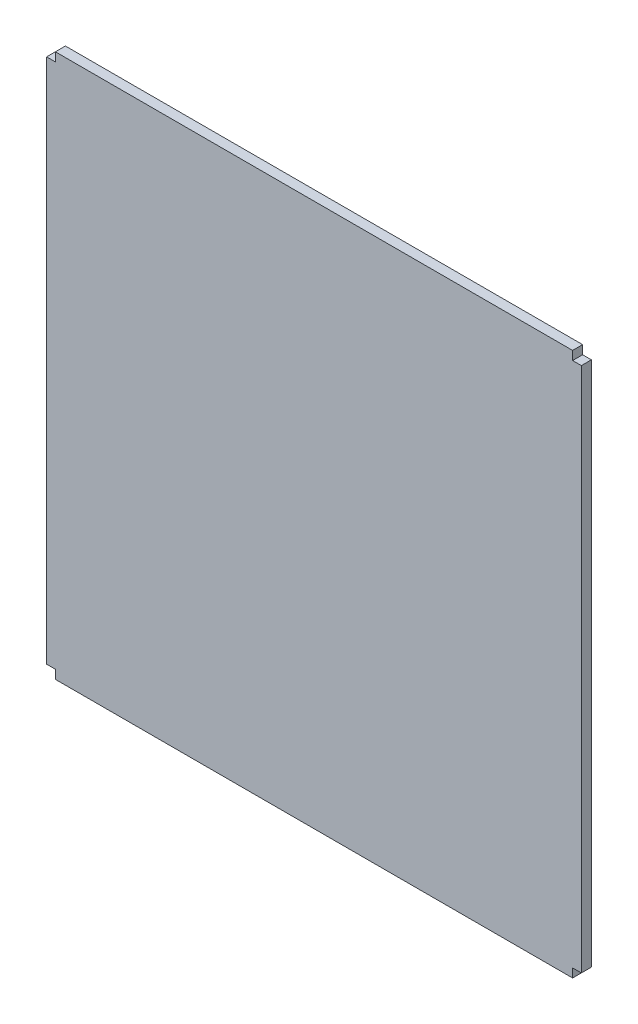
SolidWorks part; units mm, degrees
ref_plane "Ön Düzlem" through (0, 0, 0) normal (0, 0, 1) x (1, 0, 0)
ref_plane "Üst Düzlem" through (0, 0, 0) normal (0, 1, 0) x (1, 0, 0)
ref_plane "Sağ Düzlem" through (0, 0, 0) normal (1, 0, 0) x (0, 0, -1)
sketch "Sketch1" plane through (0, 0, 0) normal (0, 0, 1) x (1, 0, 0)
  line L5 (-213.5, -217) -> (213.5, -217)
  line L6 (-213.5, -217) -> (-213.5, 217)
  line L7 (-213.5, 217) -> (213.5, 217)
  line L8 (213.5, -217) -> (213.5, 217)
  line L9 (-213.5, -217) -> (213.5, 217) construction
  line L10 (-213.5, 217) -> (213.5, -217) construction
  point P0 (0, 0)
  dimension "D1" = 427
  dimension "D2" = 434
extrude "Boss-Extrude1" add sketch "Sketch1" along normal blind 8
sketch "Sketch2" plane through (0, 0, 8) normal (0, 0, 1) x (1, 0, 0)
  line L1 (-213.5, 217) -> (-206.5, 217)
  line L2 (-213.5, 217) -> (-213.5, 210)
  line L3 (-213.5, 210) -> (-206.5, 210)
  line L4 (-206.5, 217) -> (-206.5, 210)
  dimension "D1" = 7
  dimension "D2" = 7
extrude "Cut-Extrude1" cut sketch "Sketch2" against normal blind 8
mirror "Mirror1" about plane through (0, 0, 0) normal (1, 0, 0) of "Cut-Extrude1"
mirror "Mirror2" about plane through (0, 0, 0) normal (0, 1, 0) of "Mirror1", "Cut-Extrude1"
